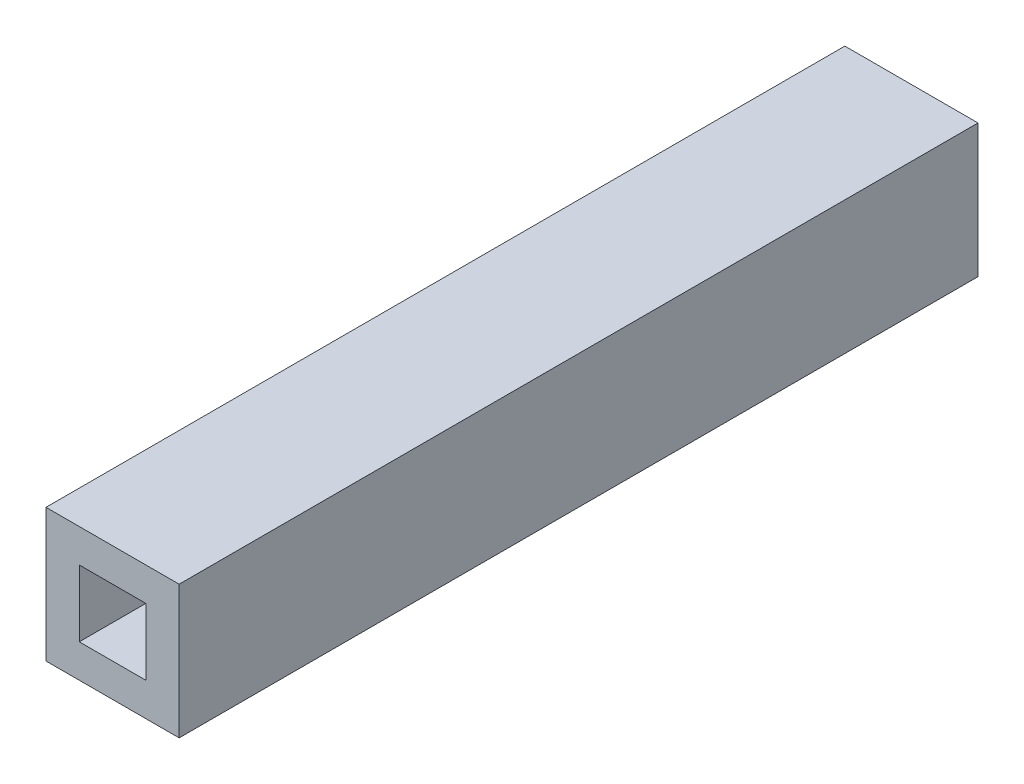
SolidWorks part; units mm, degrees
ref_plane "Front Plane" through (0, 0, 0) normal (0, 0, 1) x (1, 0, 0)
ref_plane "Top Plane" through (0, 0, 0) normal (0, 1, 0) x (1, 0, 0)
ref_plane "Right Plane" through (0, 0, 0) normal (1, 0, 0) x (0, 0, -1)
sketch "Sketch1" plane through (0, 0, 0) normal (0, 0, 1) x (1, 0, 0)
  line L1 (0, 0) -> (-25.4, 0)
  line L2 (0, 0) -> (0, 25.4)
  line L3 (0, 25.4) -> (-25.4, 25.4)
  line L4 (-25.4, 0) -> (-25.4, 25.4)
  line L5 (-19.05, 19.05) -> (-6.35, 19.05)
  line L6 (-19.05, 19.05) -> (-19.05, 6.35)
  line L7 (-19.05, 6.35) -> (-6.35, 6.35)
  line L8 (-6.35, 19.05) -> (-6.35, 6.35)
  dimension "D1" = 25.4
  dimension "D2" = 25.4
  dimension "D3" = 6.35
  dimension "D4" = 6.35
  dimension "D5" = 6.35
  dimension "D6" = 6.35
extrude "Boss-Extrude1" add sketch "Sketch1" along normal blind 152.4
